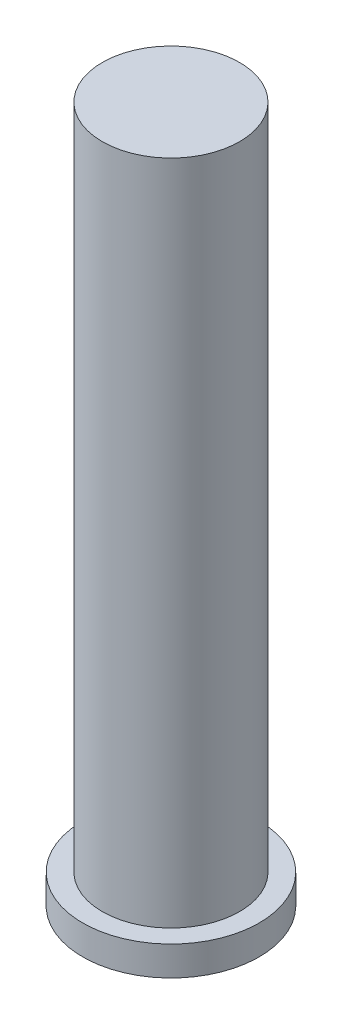
SolidWorks part; units mm, degrees
ref_plane "Front Plane" through (0, 0, 0) normal (0, 0, 1) x (1, 0, 0)
ref_plane "Top Plane" through (0, 0, 0) normal (0, 1, 0) x (1, 0, 0)
ref_plane "Right Plane" through (0, 0, 0) normal (1, 0, 0) x (0, 0, -1)
sketch "Sketch1" plane through (0, 0, 0) normal (0, 1, 0) x (1, 0, 0)
  circle A0 centre (0, 0) radius 2.286
  dimension "D1" = 4.572
extrude "Boss-Extrude1" add sketch "Sketch1" along normal blind 0.762
sketch "Sketch2" plane through (0, 0.762, 0) normal (0, 1, 0) x (1, 0, 0)
  circle A0 centre (0, 0) radius 1.778
  dimension "D1" = 3.556
extrude "Boss-Extrude2" add sketch "Sketch2" along normal blind 17.272
